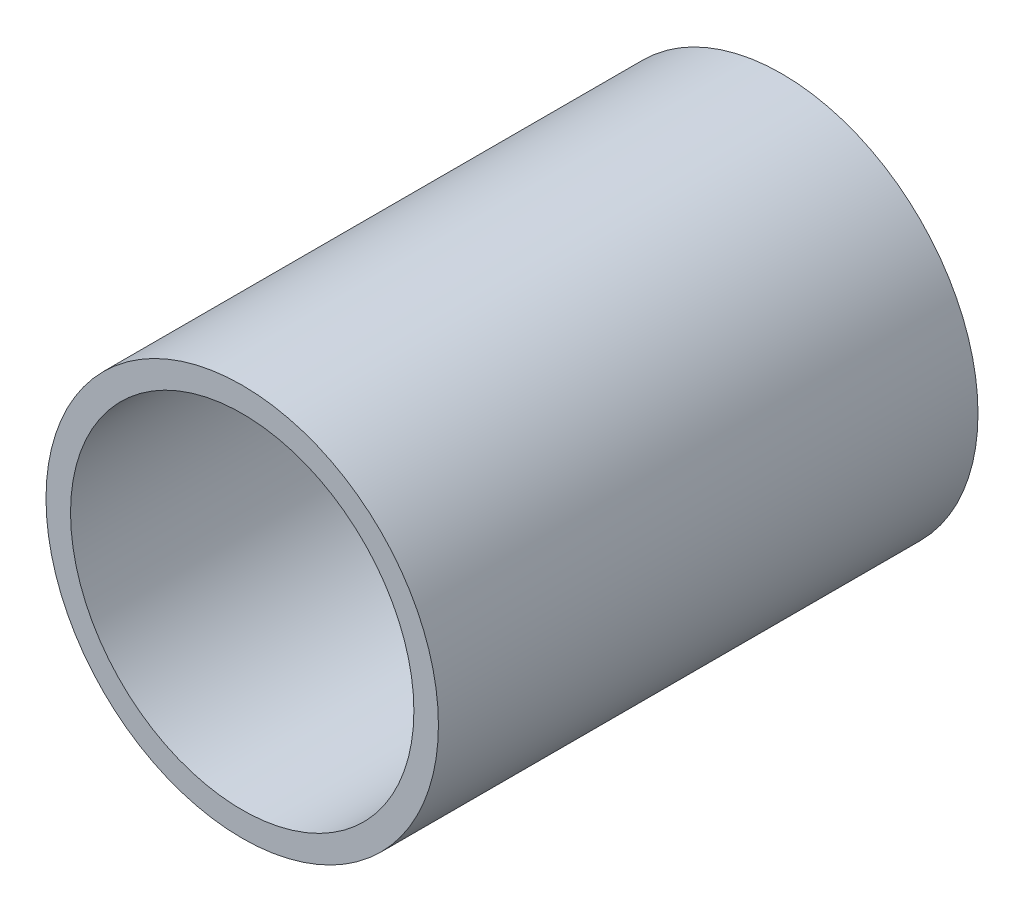
SolidWorks part; units mm, degrees
ref_plane "Front Plane" through (0, 0, 0) normal (0, 0, 1) x (1, 0, 0)
ref_plane "Top Plane" through (0, 0, 0) normal (0, 1, 0) x (1, 0, 0)
ref_plane "Right Plane" through (0, 0, 0) normal (1, 0, 0) x (0, 0, -1)
sketch "Sketch1" plane through (0, 0, 0) normal (0, 0, 1) x (1, 0, 0)
  circle A0 centre (0, 0) radius 40
  circle A1 centre (0, 0) radius 35
  dimension "D1" = 80
  dimension "D2" = 70
extrude "Boss-Extrude1" add sketch "Sketch1" along normal blind 110
